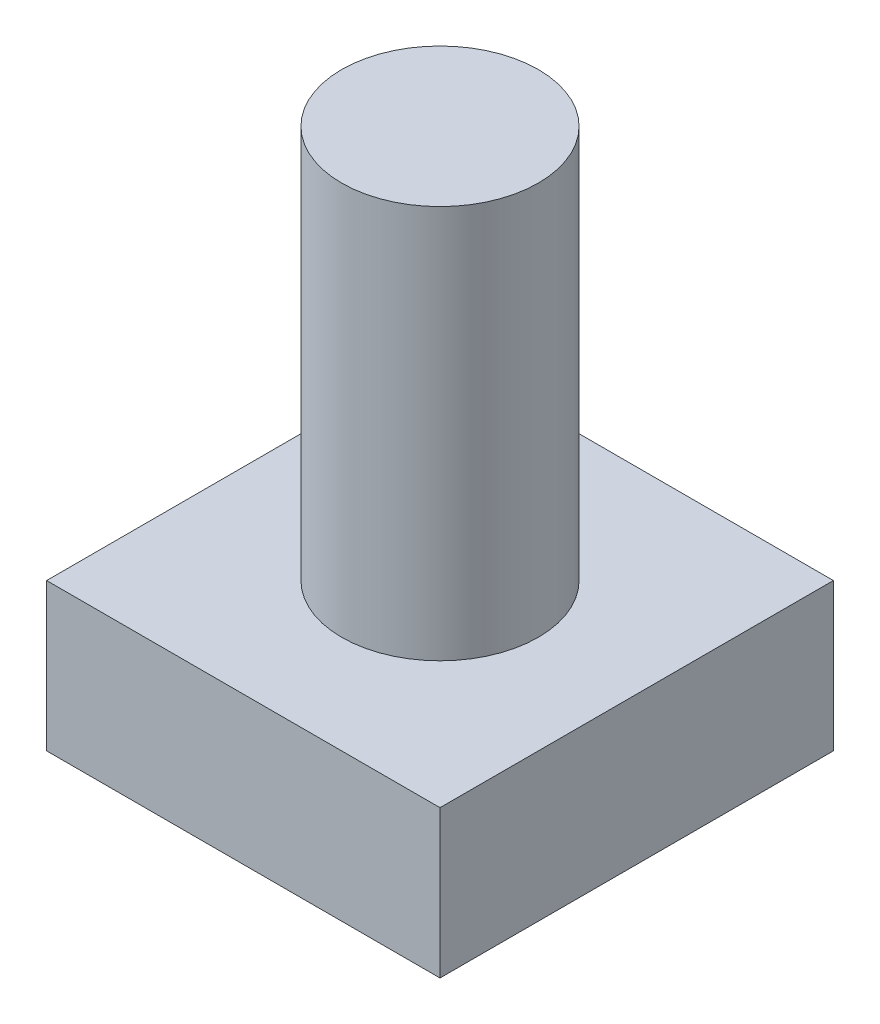
SolidWorks part; units mm, degrees
ref_plane "Front Plane" through (0, 0, 0) normal (0, 0, 1) x (1, 0, 0)
ref_plane "Top Plane" through (0, 0, 0) normal (0, 1, 0) x (1, 0, 0)
ref_plane "Right Plane" through (0, 0, 0) normal (1, 0, 0) x (0, 0, -1)
sketch "Sketch1" plane through (0, 0, 0) normal (0, 0, 1) x (1, 0, 0)
  line L1 (-2, 0.75) -> (2, 0.75)
  line L2 (-2, 0.75) -> (-2, -0.75)
  line L3 (-2, -0.75) -> (2, -0.75)
  line L4 (2, 0.75) -> (2, -0.75)
  line L5 (-2, 0.75) -> (2, -0.75) construction
  line L6 (-2, -0.75) -> (2, 0.75) construction
  point P0 (0, 0)
  dimension "D1" = 4
  dimension "D2" = 1.5
extrude "Boss-Extrude1" add sketch "Sketch1" along normal blind 4
sketch "Sketch2" plane through (0, 0.75, 0) normal (0, 1, 0) x (1, 0, 0)
  circle A0 centre (0, -2) radius 1
extrude "Boss-Extrude2" add sketch "Sketch2" along normal blind 4
